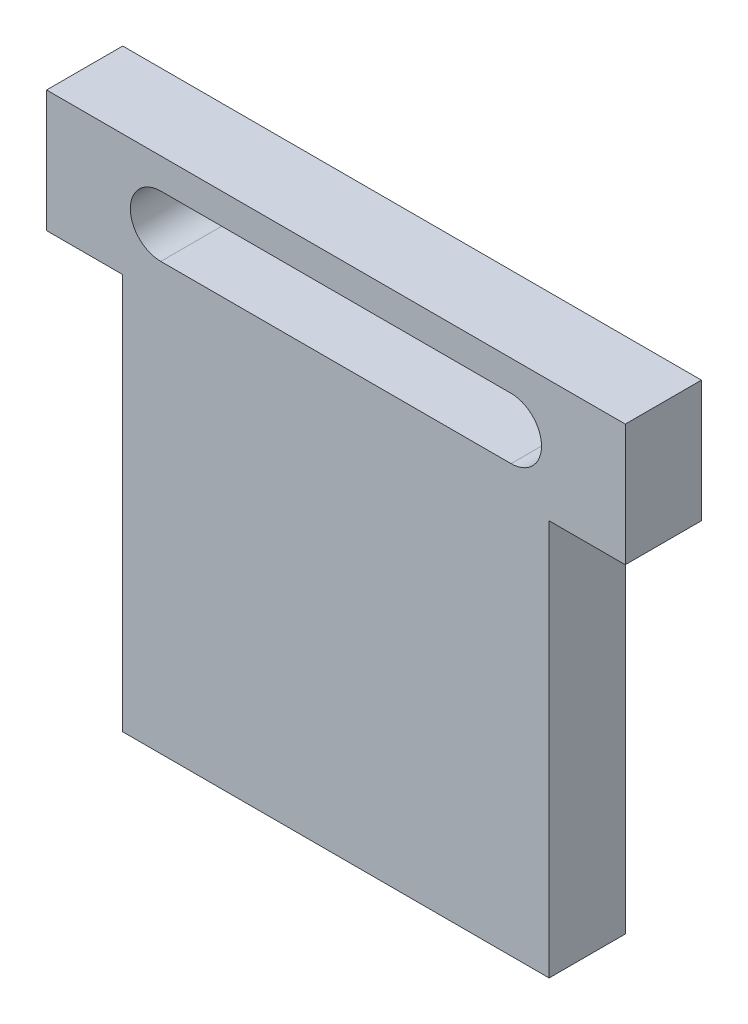
SolidWorks part; units mm, degrees
ref_plane "Plan de face" through (0, 0, 0) normal (0, 0, 1) x (1, 0, 0)
ref_plane "Plan de dessus" through (0, 0, 0) normal (0, 1, 0) x (1, 0, 0)
ref_plane "Plan de droite" through (0, 0, 0) normal (1, 0, 0) x (0, 0, -1)
sketch "Esquisse1" plane through (0, 0, 0) normal (0, 0, 1) x (1, 0, 0)
  line L0 (-19, 36.5) -> (19, 36.5)
  line L1 (19, 36.5) -> (19, 28.5)
  line L2 (19, 28.5) -> (14, 28.5)
  line L3 (14, 28.5) -> (14, 2.5)
  line L4 (14, 2.5) -> (-14, 2.5)
  line L5 (-14, 2.5) -> (-14, 28.5)
  line L6 (-14, 28.5) -> (-19, 28.5)
  line L7 (-19, 28.5) -> (-19, 36.5)
extrude "Corps_verrou_guillotine" add sketch "Esquisse1" against normal blind 5 from offset 4.5
sketch "Esquisse2" plane through (0, 0, 0) normal (0, 0, 1) x (1, 0, 0)
  line L0 (-11.5, 34.5) -> (11.5, 34.5)
  line L1 (11.5, 30.5) -> (-11.5, 30.5)
  arc A0 (11.5, 34.5) -> (11.5, 30.5) centre (11.5, 32.5) cw
  arc A1 (-11.5, 30.5) -> (-11.5, 34.5) centre (-11.5, 32.5) cw
extrude "Lumiere_oblongue_manivelle" cut sketch "Esquisse2" against normal through all and the other way through all
